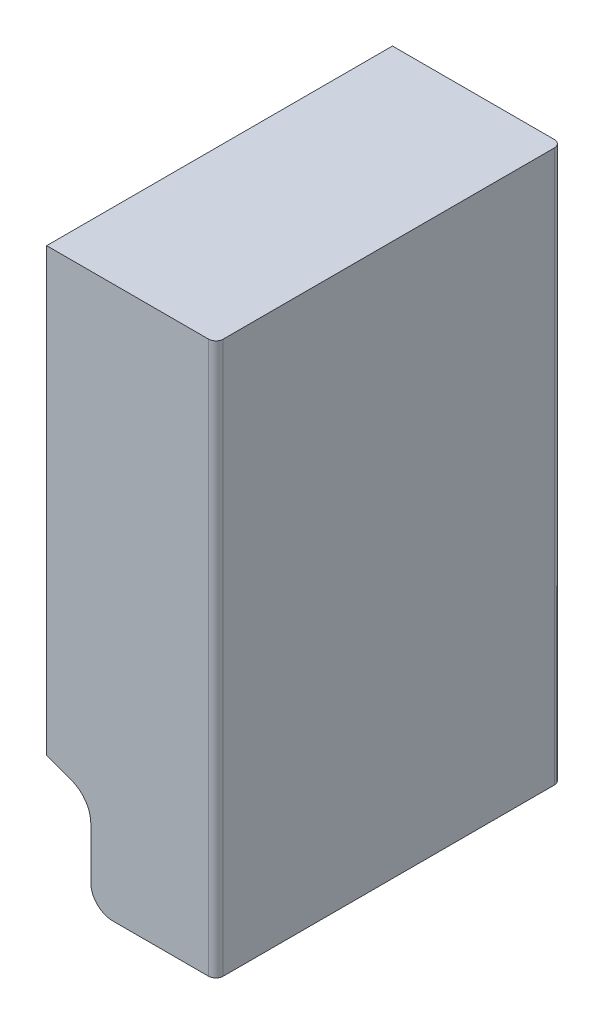
SolidWorks part; units mm, degrees
material "K110"
ref_plane "Front Plane" through (0, 0, 0) normal (0, 0, 1) x (1, 0, 0)
ref_plane "Top Plane" through (0, 0, 0) normal (0, 1, 0) x (1, 0, 0)
ref_plane "Right Plane" through (0, 0, 0) normal (1, 0, 0) x (0, 0, -1)
sketch "Sketch1" plane through (0, 0, 0) normal (0, 1, 0) x (1, 0, 0)
  line L1 (-11.5, -23.5) -> (11.5, -23.5)
  line L2 (-11.5, -23.5) -> (-11.5, 23.5)
  line L3 (-11.5, 23.5) -> (11.5, 23.5)
  line L4 (11.5, -23.5) -> (11.5, 23.5)
  line L5 (-11.5, -23.5) -> (11.5, 23.5) construction
  line L6 (-11.5, 23.5) -> (11.5, -23.5) construction
  point P0 (0, 0)
  dimension "D1" = 23
  dimension "D2" = 47
extrude "Boss-Extrude1" add sketch "Sketch1" against normal blind 75
sketch "Sketch2" plane through (0, 0, 23.5) normal (0, 0, 1) x (1, 0, 0)
  line L0 (-11.5, 0) -> (11.5, 0) construction
  line L1 (-11.5, -75) -> (-5.5, -75) construction
  line L2 (-11.5, -75) -> (-11.5, -61) construction
  line L3 (-11.5, -61) -> (-9.5, -61) construction
  line L4 (-5.5, -75) -> (-5.5, -65) construction
  line L5 (11.5, -75) -> (11.5, 0) construction
  line L6 (-8.1319, -61.2412) -> (-11.5, -60.0153)
  line L7 (-11.5, -75) -> (-11.5, 0) construction
  line L8 (-5.5, -65) -> (-5.5, -75)
  line L9 (-5.5, -75) -> (-11.5, -75)
  line L10 (-11.5, -75) -> (-11.5, -60.0153)
  arc A0 (-9.5, -61) -> (-5.5, -65) centre (-9.5, -65) cw construction
  arc A1 (-5.5, -65) -> (-8.1319, -61.2412) centre (-9.5, -65) ccw
  dimension "D3" = 4
  dimension "D1" = 61
  dimension "D2" = 17
  dimension "D4" = 2
  dimension "D5" = 20
extrude "Cut-Extrude1" cut sketch "Sketch2" against normal up to next
fillet "Fillet1" radius 3 1 edges at (-5.5, -75, 0)
fillet "Fillet2" radius 1 2 edges at (11.5, -37.5, -23.5) (11.5, -37.5, 23.5)
